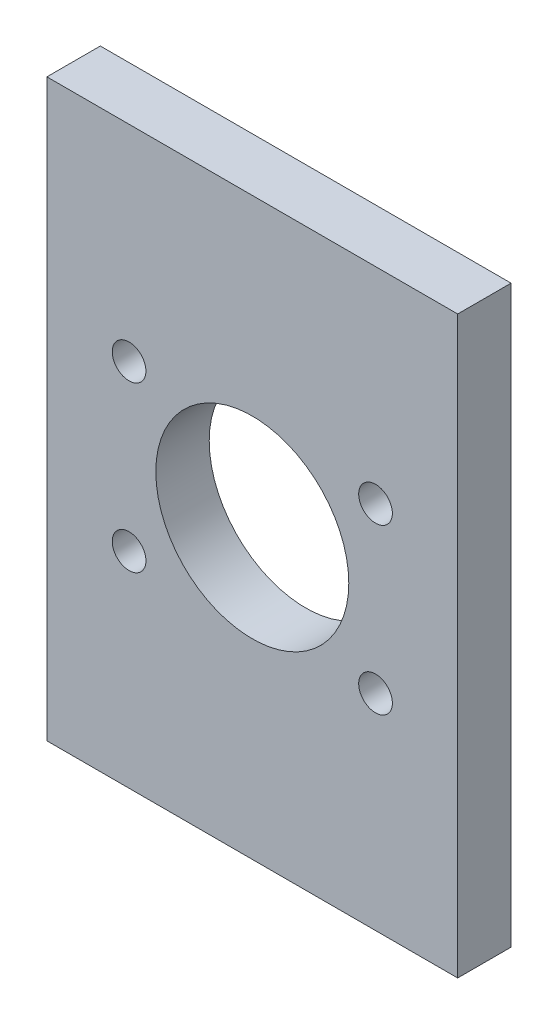
SolidWorks part; units mm, degrees
ref_plane "Front Plane" through (0, 0, 0) normal (0, 0, 1) x (1, 0, 0)
ref_plane "Top Plane" through (0, 0, 0) normal (0, 1, 0) x (1, 0, 0)
ref_plane "Right Plane" through (0, 0, 0) normal (1, 0, 0) x (0, 0, -1)
sketch "Sketch1" plane through (0, 0, 0) normal (0, 0, 1) x (1, 0, 0)
  line L1 (-50, 70) -> (50, 70)
  line L2 (-50, 70) -> (-50, -70)
  line L3 (-50, -70) -> (50, -70)
  line L4 (50, 70) -> (50, -70)
  line L5 (-50, 70) -> (50, -70) construction
  line L6 (-50, -70) -> (50, 70) construction
  circle A0 centre (0, 0) radius 23.49
  point P0 (0, 0)
  dimension "D3" = 46.98
  dimension "D1" = 100
  dimension "D2" = 140
extrude "Boss-Extrude1" add sketch "Sketch1" along normal blind 13
sketch "Sketch5" plane through (0, 0, 13) normal (0, 0, 1) x (1, 0, 0)
  line L0 (0, 70) -> (0, -70) construction
  line L1 (50, 70) -> (-50, 70) construction
  line L2 (-50, -70) -> (50, -70) construction
  line L3 (-50, 0) -> (50, 0) construction
  line L4 (-50, 70) -> (-50, -70) construction
  line L5 (50, -70) -> (50, 70) construction
  point P12 (-30, 20)
  point P13 (30, 20)
  point P14 (30, -20)
  point P15 (-30, -20)
  dimension "D1" = 40
  dimension "D2" = 60
hole_wizard "M8 Clearance Hole1" positions "3DSketch3" profile "Sketch6" hole size "M8" standard "ANSI Metric"
sketch3d "3DSketch3"
  point P0 (-30, 20, 13)
  point P3 (30, 20, 13)
  point P6 (30, -20, 13)
  point P9 (-30, -20, 13)
sketch "Sketch6" plane through (-30, 20, 13) normal (1, 0, 0) x (0, -1, 0)
  line L0 (0, 0) -> (0, 22.2135)
  line L1 (0, 22.2135) -> (4.1, 19.75)
  line L2 (4.1, 19.75) -> (4.1, 0)
  line L5 (4.1, 0) -> (0, 0)
  line L10 (0, 22.2135) -> (-4.1, 19.75) construction
  line L11 (0, -6.35) -> (0, 107.95) construction
  dimension "Hole Dia." = 8.2
  dimension "Hole Depth" = 19.75
  dimension "Drill Angle" = 118
